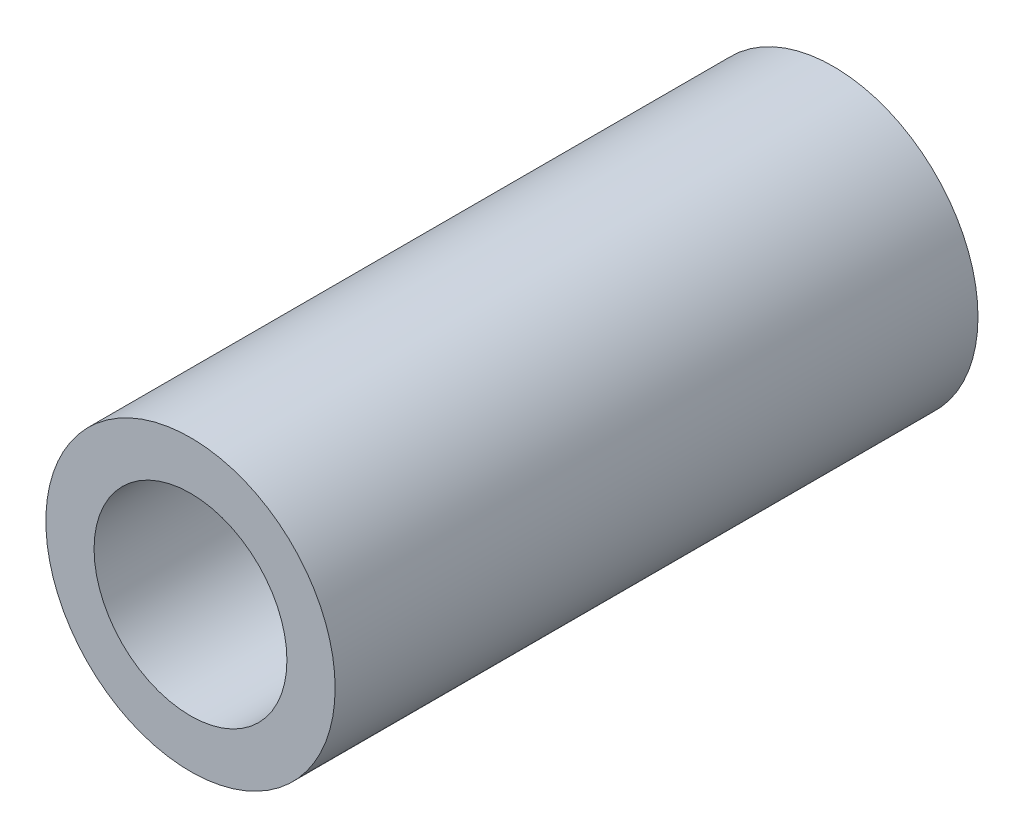
SolidWorks part; units mm, degrees
ref_plane "Front Plane" through (0, 0, 0) normal (0, 0, 1) x (1, 0, 0)
ref_plane "Top Plane" through (0, 0, 0) normal (0, 1, 0) x (1, 0, 0)
ref_plane "Right Plane" through (0, 0, 0) normal (1, 0, 0) x (0, 0, -1)
sketch "Sketch1" plane through (0, 0, 0) normal (0, 0, 1) x (1, 0, 0)
  circle A0 centre (0, 0) radius 2.25
  circle A1 centre (0, 0) radius 1.5
  dimension "D1" = 4.5
  dimension "D2" = 3
extrude "Boss-Extrude1" add sketch "Sketch1" along normal blind 10
